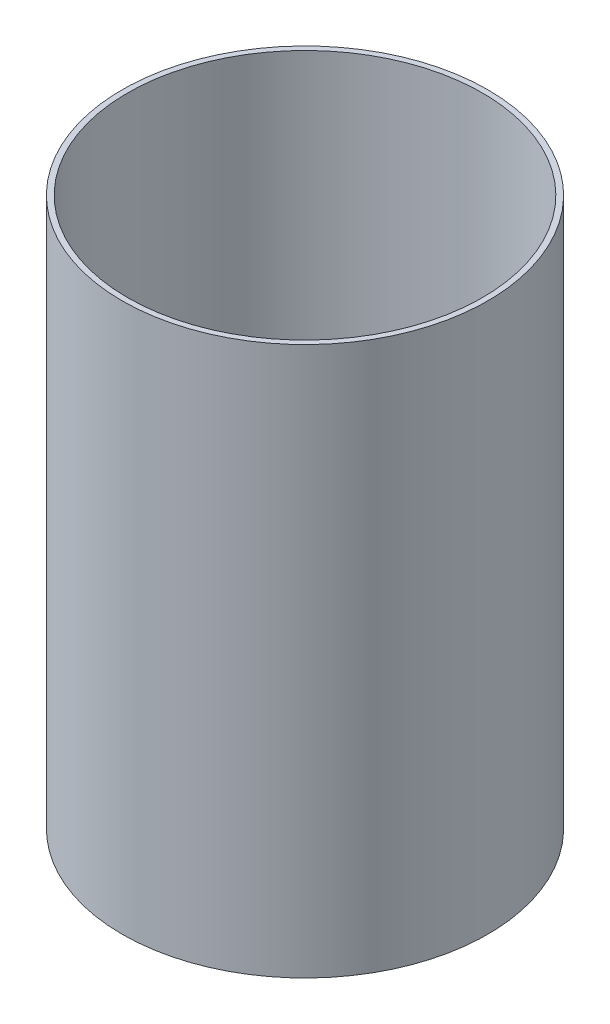
SolidWorks part; units mm, degrees
ref_plane "Front Plane" through (0, 0, 0) normal (0, 0, 1) x (1, 0, 0)
ref_plane "Top Plane" through (0, 0, 0) normal (0, 1, 0) x (1, 0, 0)
ref_plane "Right Plane" through (0, 0, 0) normal (1, 0, 0) x (0, 0, -1)
sketch "Sketch1" plane through (0, 0, 0) normal (0, 1, 0) x (1, 0, 0)
  circle A0 centre (0, 0) radius 100
  circle A1 centre (0, 0) radius 97
  dimension "D1" = 200
  dimension "D2" = 3
extrude "Boss-Extrude1" add sketch "Sketch1" along normal blind 300
